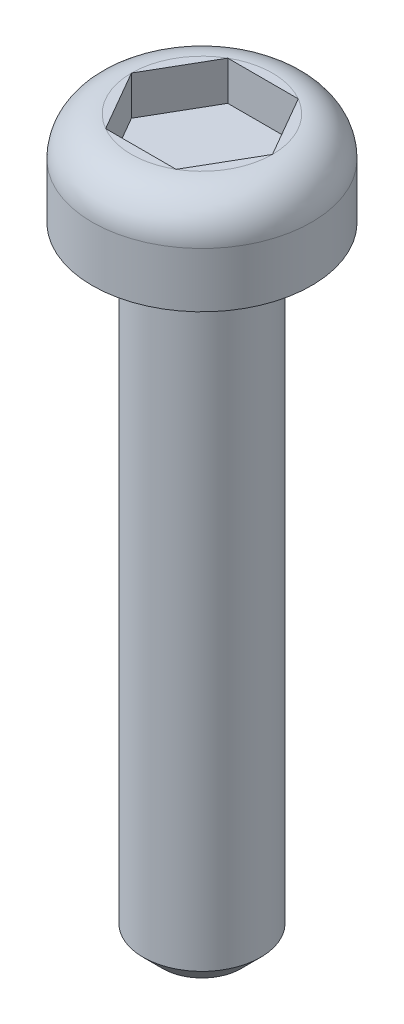
SolidWorks part; units mm, degrees
ref_plane "Front" through (0, 0, 0) normal (0, 0, 1) x (1, 0, 0)
ref_plane "Top" through (0, 0, 0) normal (0, 1, 0) x (1, 0, 0)
ref_plane "Right" through (0, 0, 0) normal (1, 0, 0) x (0, 0, -1)
sketch "Sketch1" plane through (0, 0, 0) normal (0, 1, 0) x (1, 0, 0)
  circle A0 centre (0, 0) radius 1.5
  dimension "D1" = 3
extrude "Boss-Extrude1" add sketch "Sketch1" along normal blind 16
cosmetic thread "Cosmetic Thread1" parameters "D2"=2
sketch "Sketch2" plane through (0, 16, 0) normal (0, 1, 0) x (1, 0, 0)
  circle A0 centre (0, 0) radius 2.8
  dimension "D1" = 5.6
extrude "Boss-Extrude2" add sketch "Sketch2" along normal blind 2.4
fillet "Fillet1" radius 1 1 edges at (0, 18.4, 2.8)
sketch "Sketch3" plane through (0, 18.4, 0) normal (0, 1, 0) x (1, 0, 0)
  line L1 (1.8, 0) -> (0.9, 1.5588)
  line L2 (0.9, 1.5588) -> (-0.9, 1.5588)
  line L3 (-0.9, 1.5588) -> (-1.8, 0)
  line L4 (-1.8, 0) -> (-0.9, -1.5588)
  line L5 (-0.9, -1.5588) -> (0.9, -1.5588)
  line L6 (0.9, -1.5588) -> (1.8, 0)
  circle A0 centre (0, 0) radius 1.5588 construction
  circle A1 centre (0, 0) radius 1.8 construction
extrude "Cut-Extrude1" cut sketch "Sketch3" against normal blind 1
chamfer "Chamfer1" distance 0.5 angle 45 1 edges at (0, 0, 1.5)
